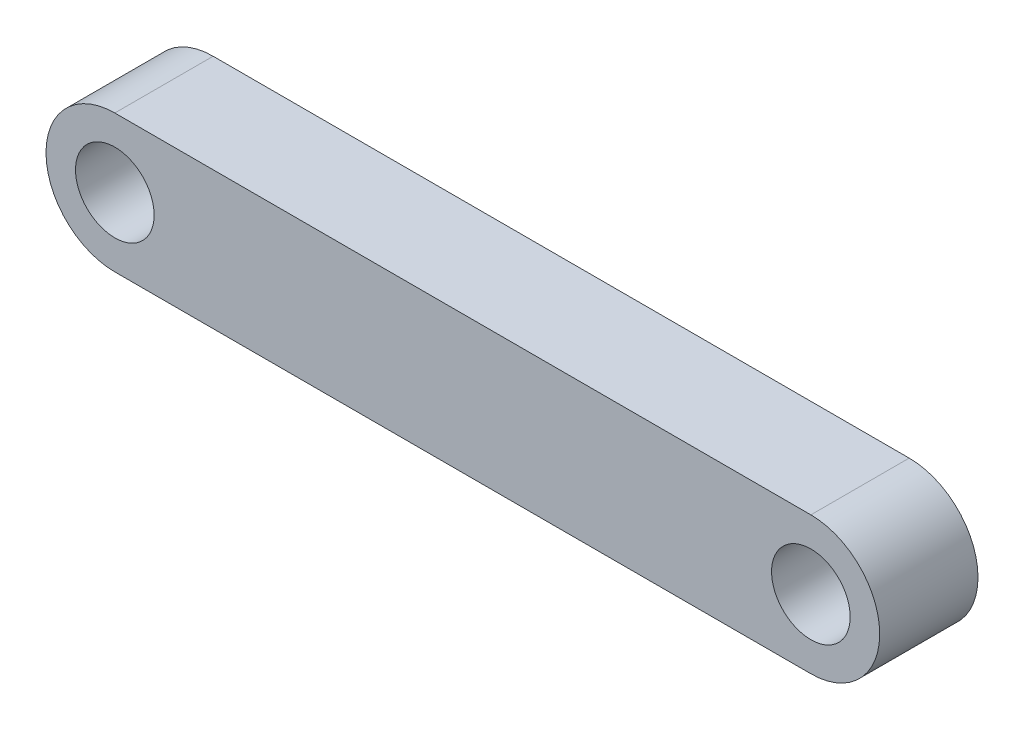
SolidWorks part; units mm, degrees
ref_plane "前视基准面" through (0, 0, 0) normal (0, 0, 1) x (1, 0, 0)
ref_plane "上视基准面" through (0, 0, 0) normal (0, 1, 0) x (1, 0, 0)
ref_plane "右视基准面" through (0, 0, 0) normal (1, 0, 0) x (0, 0, -1)
other "Configuration Table"
sketch "草图2" plane through (0, 0, 0) normal (0, 0, 1) x (1, 0, 0)
  line L0 (0, 0) -> (354, 0)
  line L1 (0, 35) -> (354, 35)
  line L3 (354, -35) -> (0, -35)
  arc A0 (0, 35) -> (0, -35) centre (0, 0) ccw
  arc A1 (354, -35) -> (354, 35) centre (354, 0) ccw
  circle A2 centre (0, 0) radius 20
  circle A3 centre (354, 0) radius 20
  dimension "D1" = 35
  dimension "D2" = 40
  dimension "D3" = 40
  dimension "D4" = 354
extrude "凸台-拉伸1" add sketch "草图2" along normal blind 50
